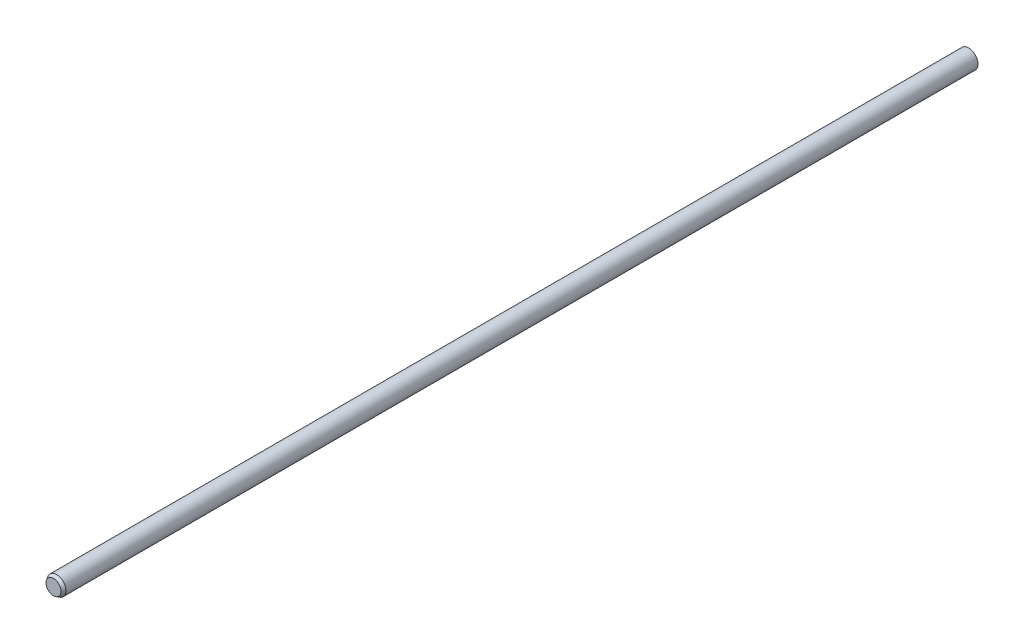
SolidWorks part; units mm, degrees
material "1060 Alloy"
ref_plane "Front Plane" through (0, 0, 0) normal (0, 0, 1) x (1, 0, 0)
ref_plane "Top Plane" through (0, 0, 0) normal (0, 1, 0) x (1, 0, 0)
ref_plane "Right Plane" through (0, 0, 0) normal (1, 0, 0) x (0, 0, -1)
sketch "Sketch1" plane through (0, 0, 0) normal (0, 0, 1) x (1, 0, 0)
  circle A0 centre (0, 0) radius 3
extrude "Boss-Extrude1" add sketch "Sketch1" along normal blind 295
chamfer "Chamfer1" distance 1 angle 30 2 edges at (3, 0, 295) (3, 0, 0)
